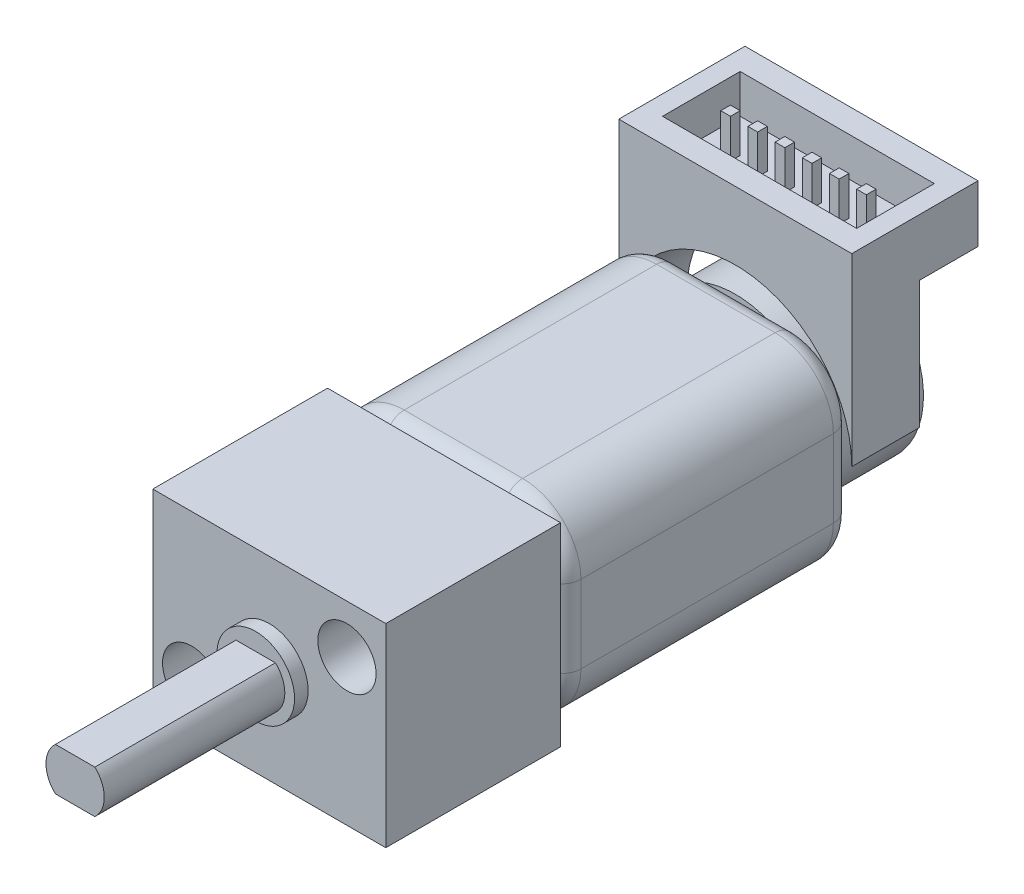
SolidWorks part; units mm, degrees
ref_plane "Front Plane" through (0, 0, 0) normal (0, 0, 1) x (1, 0, 0)
ref_plane "Top Plane" through (0, 0, 0) normal (0, 1, 0) x (1, 0, 0)
ref_plane "Right Plane" through (0, 0, 0) normal (1, 0, 0) x (0, 0, -1)
sketch "草图3" plane through (0, 0, 0) normal (0, 0, 1) x (1, 0, 0)
  line L1 (-6.05, -5) -> (6.05, -5)
  line L2 (-6.05, -5) -> (-6.05, 5)
  line L3 (-6.05, 5) -> (6.05, 5)
  line L4 (6.05, -5) -> (6.05, 5)
  line L5 (-6.05, -5) -> (6.05, 5) construction
  line L6 (-6.05, 5) -> (6.05, -5) construction
  point P0 (0, 0)
  dimension "D1" = 12.1
  dimension "D2" = 10
extrude "凸台-拉伸2" add sketch "草图3" along normal blind 15
fillet "圆角3" radius 3 4 edges at (-6.05, -5, 7.5) (-6.05, 5, 7.5) (6.05, -5, 7.5) (6.05, 5, 7.5)
fillet "圆角4" radius 1 16 edges at (5.1713, -4.1213, 0) (6.05, 0, 0) (5.1713, 4.1213, 0) (0, 5, 0) (-5.1713, 4.1213, 0) (-6.05, 0, 0) (-5.1713, -4.1213, 0) (0, -5, 0) (-5.1713, 4.1213, 15) (0, 5, 15) (5.1713, 4.1213, 15) (6.05, 0, 15) (5.1713, -4.1213, 15) (0, -5, 15) (-5.1713, -4.1213, 15) (-6.05, 0, 15)
sketch "草图4" plane through (0, 0, 15) normal (0, 0, 1) x (1, 0, 0)
  line L1 (-6, -5) -> (6, -5)
  line L2 (-6, -5) -> (-6, 5)
  line L3 (-6, 5) -> (6, 5)
  line L4 (6, -5) -> (6, 5)
  line L5 (-6, -5) -> (6, 5) construction
  line L6 (-6, 5) -> (6, -5) construction
  point P0 (0, 0)
  dimension "D1" = 10
  dimension "D2" = 12
extrude "凸台-拉伸3" add sketch "草图4" along normal blind 9
sketch "草图5" plane through (0, 0, 24) normal (0, 0, 1) x (1, 0, 0)
  circle A0 centre (0, 0) radius 2
  dimension "D1" = 4
extrude "凸台-拉伸4" add sketch "草图5" along normal blind 0.7
sketch "草图6" plane through (0, 0, 24.7) normal (0, 0, 1) x (1, 0, 0)
  circle A0 centre (0, 0) radius 1.5
  dimension "D1" = 3
extrude "凸台-拉伸5" add sketch "草图6" along normal blind 9.3
hole_wizard "Ø3.0 (3) 直径孔1" positions "草图8" profile "草图9" hole size "Ø3.0" standard "GB"
sketch "草图8" plane through (0, 0, 24) normal (0, 0, 1) x (1, 0, 0)
  line L0 (-6, 5) -> (-6, -5) construction
  line L2 (-6, -5) -> (6, -5) construction
  line L3 (6, -5) -> (6, 5) construction
  line L4 (6, 5) -> (-6, 5) construction
  point P4 (-4, -2.5)
  point P19 (4, 2.5)
  dimension "D1" = 2
  dimension "D2" = 2.5
  dimension "D3" = 2
  dimension "D4" = 2.5
sketch "草图9" plane through (-4, -2.5, 24) normal (1, 0, 0) x (0, -1, 0)
  line L0 (0, 0) -> (0, 3.4013)
  line L1 (0, 3.4013) -> (1.5, 2.5)
  line L2 (1.5, 2.5) -> (1.5, 0)
  line L5 (1.5, 0) -> (0, 0)
  line L10 (0, 3.4013) -> (-1.5, 2.5) construction
  line L11 (0, -6.35) -> (0, 107.95) construction
  dimension "孔直径" = 3
  dimension "孔深度" = 2.5
  dimension "导头角度" = 118
sketch "草图10" plane through (0, 0, 0) normal (0, 0, -1) x (-1, 0, 0)
  line L0 (-1000, 0) -> (49000, 0) construction
  line L1 (0, -1000) -> (0, 49000) construction
  line L2 (-6, 0) -> (-6, 9.5)
  line L3 (-6, 9.5) -> (6, 9.5)
  line L4 (6, 9.5) -> (6, 0)
  arc A2 (6, 0) -> (-6, 0) centre (0, 0) ccw
  dimension "D1" = 9.5
extrude "凸台-拉伸7" add sketch "草图10" along normal blind 6.5
sketch "草图11" plane through (0, 0, 0) normal (0, 0, -1) x (-1, 0, 0)
  circle A0 centre (0, 0) radius 4.6929
extrude "凸台-拉伸8" add sketch "草图11" along normal blind 5
sketch "草图12" plane through (0, 0, -6.5) normal (0, 0, -1) x (-1, 0, 0)
  line L0 (-6, 0) -> (-6, 6.5652)
  line L1 (-6, 9.5) -> (-6, 0) construction
  line L2 (-6, 6.5652) -> (6, 6.5652)
  line L3 (6, 0) -> (6, 9.5) construction
  line L4 (6, 6.5652) -> (6, 0)
  arc A0 (6, 0) -> (-6, 0) centre (0, 0) ccw construction
  arc A1 (6, 0) -> (-6, 0) centre (0, 0) ccw
extrude "切除-拉伸1" cut sketch "草图12" against normal blind 3
sketch "草图13" plane through (0, 9.5, 0) normal (0, 1, 0) x (1, 0, 0)
  line L1 (-5, 1.25) -> (5, 1.25)
  line L2 (-5, 1.25) -> (-5, 5.25)
  line L3 (-5, 5.25) -> (5, 5.25)
  line L4 (5, 1.25) -> (5, 5.25)
  line L5 (-5, 1.25) -> (5, 5.25) construction
  line L6 (-5, 5.25) -> (5, 1.25) construction
  line L8 (-1000, 3.25) -> (49000, 3.25) construction
  line L9 (-6, 6.5) -> (6, 6.5) construction
  line L10 (-6, 0) -> (6, 0) construction
  point P0 (0, 3.25)
  dimension "D1" = 4
  dimension "D2" = 10
extrude "切除-拉伸2" cut sketch "草图13" against normal blind 2
sketch "草图14" plane through (0, 7.5, 0) normal (0, 1, 0) x (1, 0, 0)
  line L0 (-1000.2804, 3.25) -> (999.9916, 3.25) construction
  line L6 (-0.95, 3) -> (-0.45, 3)
  line L7 (0, -1000) -> (0, 49000) construction
  line L8 (-6, 6.5) -> (6, 6.5) construction
  line L9 (-6, 0) -> (6, 0) construction
  line L10 (-0.95, 3) -> (-0.95, 3.5)
  line L11 (-0.95, 3.5) -> (-0.45, 3.5)
  line L12 (-0.45, 3) -> (-0.45, 3.5)
  line L13 (-0.95, 3) -> (-0.45, 3.5) construction
  line L14 (-0.95, 3.5) -> (-0.45, 3) construction
  point P0 (-0.7, 3.25)
  point P8 (0, 0)
  point P17 (-4.7914, 3.25)
  dimension "D1" = 0.7
  dimension "D2" = 0.5
  dimension "D3" = 0.5
extrude "凸台-拉伸9" add sketch "草图14" along normal blind 2
pattern_linear "阵列(线性)1" count 3 spacing 1.4 along (-1, 0, 0) count 4 spacing 1.4 along (1, 0, 0) of "凸台-拉伸9"
sketch "草图15" plane through (0, 0, 34) normal (0, 0, 1) x (1, 0, 0)
  line L0 (-1.0144, 1.1049) -> (1.0144, 1.1049)
  line L1 (-1000, 0) -> (49000, 0) construction
  line L2 (-1.0144, -1.1049) -> (1.0144, -1.1049)
  circle A0 centre (0, 0) radius 1.5 construction
  arc A1 (-1.0144, -1.1049) -> (1.0144, -1.1049) centre (0, 0) ccw
  arc A2 (1.0144, 1.1049) -> (-1.0144, 1.1049) centre (0, 0) ccw
  dimension "D1" = 2.2099
extrude "切除-拉伸3" cut sketch "草图15" against normal blind 9.3
equation "\"12。1\"=64.7348"
